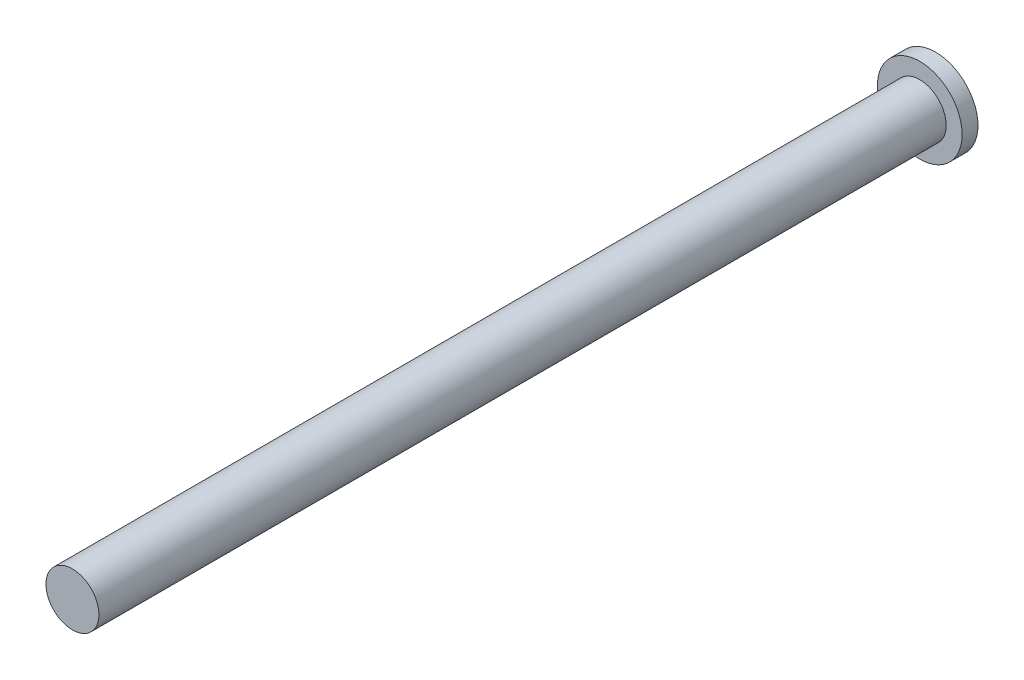
SolidWorks part; units mm, degrees
ref_plane "Front Plane" through (0, 0, 0) normal (0, 0, 1) x (1, 0, 0)
ref_plane "Top Plane" through (0, 0, 0) normal (0, 1, 0) x (1, 0, 0)
ref_plane "Right Plane" through (0, 0, 0) normal (1, 0, 0) x (0, 0, -1)
sketch "Sketch1" plane through (0, 0, 0) normal (0, 0, 1) x (1, 0, 0)
  circle A0 centre (0, 0) radius 4
  dimension "D1" = 8
extrude "Boss-Extrude1" add sketch "Sketch1" along normal blind 1.5
sketch "Sketch2" plane through (0, 0, 1.5) normal (0, 0, 1) x (1, 0, 0)
  circle A0 centre (0, 0) radius 2.5
  dimension "D1" = 5
extrude "Boss-Extrude2" add sketch "Sketch2" along normal blind 80
